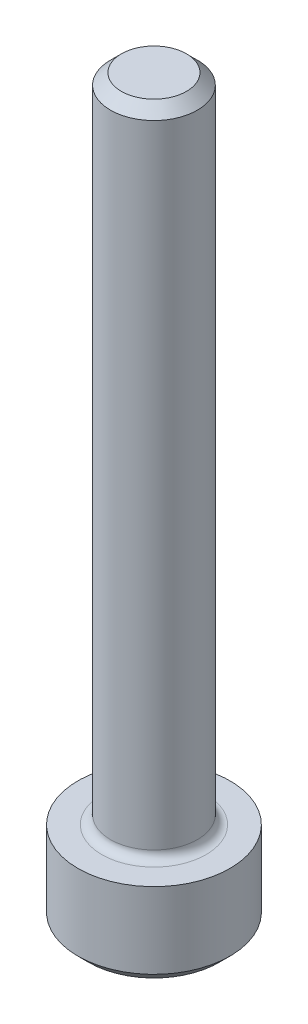
SolidWorks part; units mm, degrees
ref_plane "Front Plane" through (0, 0, 0) normal (0, 0, 1) x (1, 0, 0)
ref_plane "Top Plane" through (0, 0, 0) normal (0, 1, 0) x (1, 0, 0)
ref_plane "Right Plane" through (0, 0, 0) normal (1, 0, 0) x (0, 0, -1)
sketch "Sketch2" plane through (0, 0, 0) normal (0, 1, 0) x (1, 0, 0)
  circle A0 centre (0, 0) radius 2
extrude "Boss-Extrude1" add sketch "Sketch2" along normal blind 30
sketch "Sketch3" plane through (0, 0, 0) normal (0, 1, 0) x (1, 0, 0)
  circle A0 centre (0, 0) radius 3.5
extrude "Boss-Extrude2" add sketch "Sketch3" against normal blind 4
fillet "Fillet1" radius 0.4 1 edges at (0, 0, 2)
chamfer "Chamfer1" distance 0.5 angle 45 2 edges at (0, 30, 2) (0, -4, 3.5)
sketch "Sketch4" plane through (0, -4, 0) normal (0, -1, 0) x (1, 0, 0)
  line L1 (0, 1.7321) -> (-1.5, 0.866)
  line L2 (-1.5, 0.866) -> (-1.5, -0.866)
  line L3 (-1.5, -0.866) -> (0, -1.7321)
  line L4 (0, -1.7321) -> (1.5, -0.866)
  line L5 (1.5, -0.866) -> (1.5, 0.866)
  line L6 (1.5, 0.866) -> (0, 1.7321)
  circle A0 centre (0, 0) radius 1.5 construction
  point P1 (0, 0)
  dimension "D1" = 3
extrude "Cut-Extrude1" cut sketch "Sketch4" against normal blind 2.5
